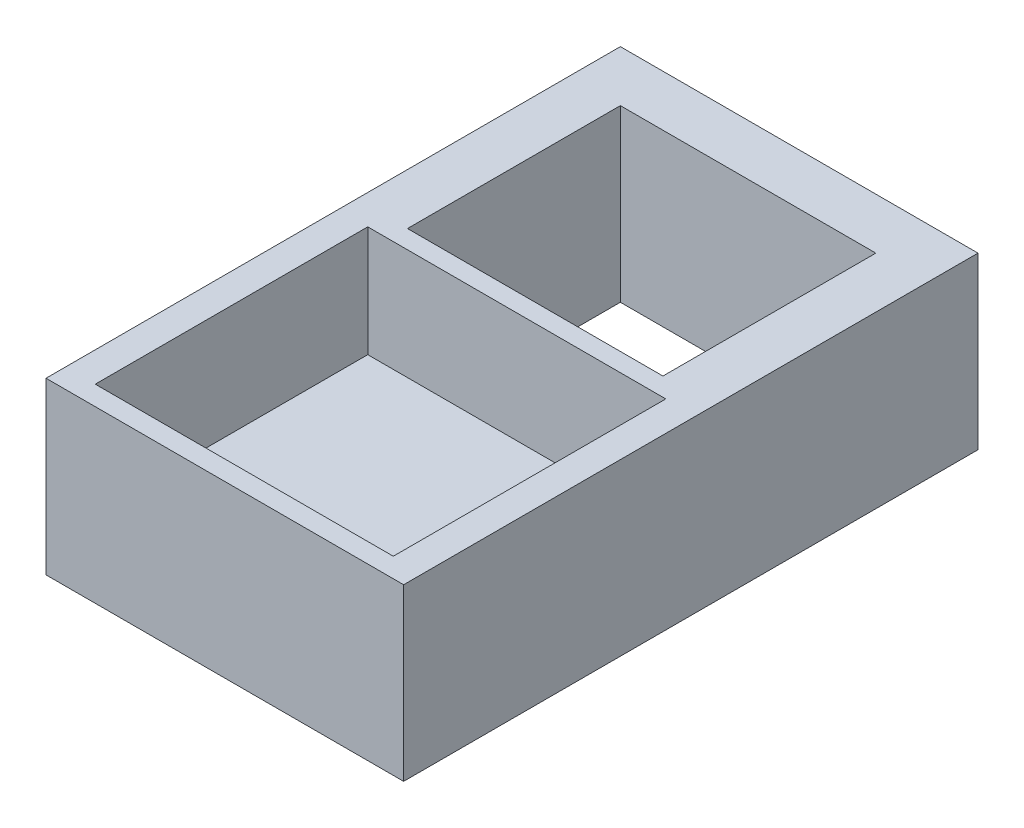
SolidWorks part; units mm, degrees
ref_plane "Front Plane" through (0, 0, 0) normal (0, 0, 1) x (1, 0, 0)
ref_plane "Top Plane" through (0, 0, 0) normal (0, 1, 0) x (1, 0, 0)
ref_plane "Right Plane" through (0, 0, 0) normal (1, 0, 0) x (0, 0, -1)
sketch "Sketch1" plane through (0, 0, 0) normal (0, 1, 0) x (1, 0, 0)
  line L0 (-18.4177, 93.376) -> (-18.4177, -114.5204) construction
  line L1 (-21.3677, -100.9619) -> (-33.4177, -100.9619)
  line L2 (-33.4177, -100.9619) -> (-33.4177, -78.5119)
  line L3 (-33.4177, -78.5119) -> (-21.3677, -78.5119)
  line L4 (-15.4677, -78.5119) -> (-21.3677, -78.5119) construction
  line L5 (-21.3677, -78.5119) -> (-21.3677, -100.9619)
  line L6 (-33.4177, -70.5119) -> (-33.4177, -45.5119)
  line L7 (-33.4177, -45.5119) -> (-18.4177, -45.5119)
  line L8 (-33.4177, -78.5119) -> (-33.4177, -70.5119) construction
  line L9 (-33.4177, -70.5119) -> (-3.4177, -70.5119)
  line L10 (-39.4177, -78.5119) -> (-39.4177, -39.5119)
  line L11 (-39.4177, -39.5119) -> (-18.4177, -39.5119)
  line L12 (-18.4177, -106.9619) -> (-39.4177, -106.9619)
  line L13 (-39.4177, -106.9619) -> (-39.4177, -78.5119)
  line L14 (-3.4177, -78.5119) -> (-3.4177, -70.5119) construction
  line L15 (2.5823, -106.9619) -> (2.5823, -78.5119)
  line L16 (-18.4177, -106.9619) -> (2.5823, -106.9619)
  line L17 (2.5823, -39.5119) -> (-18.4177, -39.5119)
  line L18 (2.5823, -78.5119) -> (2.5823, -39.5119)
  line L19 (-3.4177, -45.5119) -> (-18.4177, -45.5119)
  line L20 (-3.4177, -70.5119) -> (-3.4177, -45.5119)
  line L21 (-15.4677, -78.5119) -> (-15.4677, -100.9619)
  line L22 (-3.4177, -100.9619) -> (-3.4177, -78.5119)
  line L23 (-15.4677, -100.9619) -> (-3.4177, -100.9619)
  line L24 (-15.4677, -78.5119) -> (-3.4177, -78.5119)
  line L25 (-33.4177, -78.5119) -> (-33.4177, -45.5119) construction
  line L27 (-18.4177, -100.9619) -> (-33.4177, -100.9619) construction
  point P15 (-18.4177, -70.5119)
  point P18 (-18.4177, -78.5119)
  dimension "D1" = 6
extrude "Boss-Extrude2" add sketch "Sketch1" along normal blind 20
sketch "Sketch6" plane through (0, 20, 0) normal (0, 1, 0) x (1, 0, 0)
  line L1 (-36.6863, -73.7658) -> (-0.8222, -73.7658)
  line L2 (-36.6863, -73.7658) -> (-36.6863, -103.957)
  line L3 (-36.6863, -103.957) -> (-0.8222, -103.957)
  line L4 (-0.8222, -73.7658) -> (-0.8222, -103.957)
extrude "Boss-Extrude3" add sketch "Sketch6" against normal blind 20
sketch "Sketch7" plane through (0, 20, 0) normal (0, 1, 0) x (1, 0, 0)
  line L1 (-35.9214, -72.6728) -> (-0.9214, -72.6728)
  line L2 (-35.9214, -72.6728) -> (-35.9214, -104.6728)
  line L3 (-35.9214, -104.6728) -> (-0.9214, -104.6728)
  line L4 (-0.9214, -72.6728) -> (-0.9214, -104.6728)
  line L5 (-39.4177, -106.9619) -> (2.5823, -106.9619) construction
  line L6 (-18.4177, -106.9619) -> (-18.4177, -71.8427) construction
extrude "Cut-Extrude3" cut sketch "Sketch7" against normal blind 13
